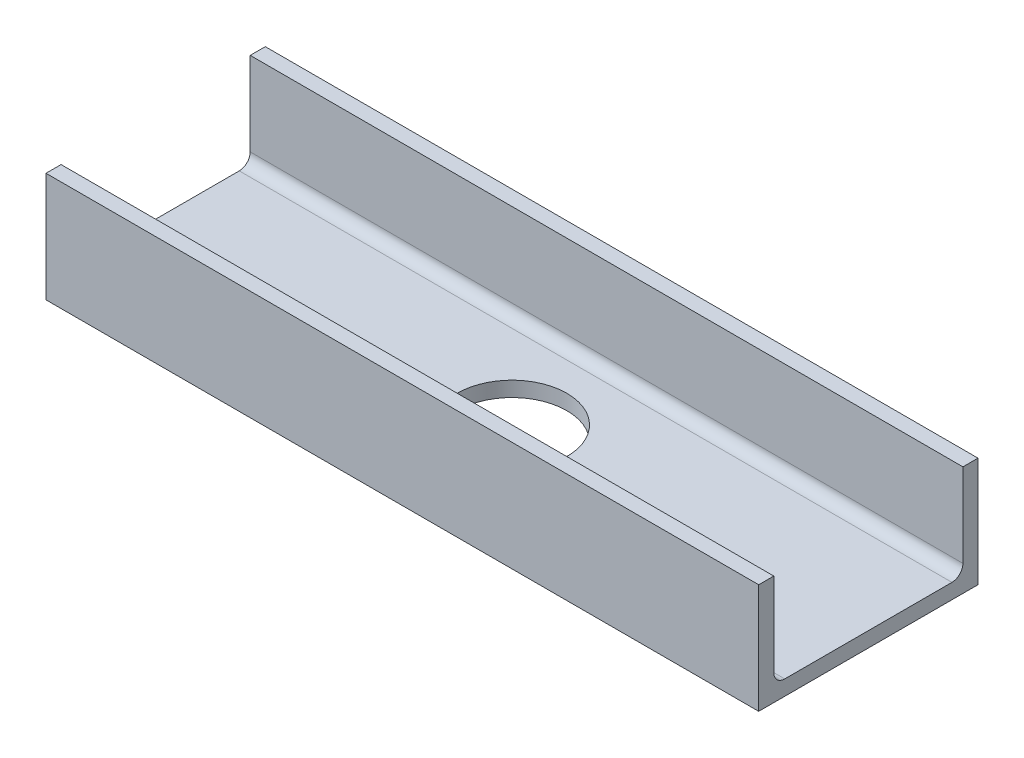
SolidWorks part; units mm, degrees
ref_plane "Front Plane" through (0, 0, 0) normal (0, 0, 1) x (1, 0, 0)
ref_plane "Top Plane" through (0, 0, 0) normal (0, 1, 0) x (1, 0, 0)
ref_plane "Right Plane" through (0, 0, 0) normal (1, 0, 0) x (0, 0, -1)
sketch "Sketch1" plane through (0, 0, 0) normal (1, 0, 0) x (0, 0, -1)
  line L0 (-21.9075, 9.2075) -> (21.9075, 9.2075)
  line L1 (-25.4, -12.7) -> (25.4, -12.7)
  line L2 (-25.4, -12.7) -> (-25.4, 12.7)
  line L3 (-25.4, 12.7) -> (25.4, 12.7)
  line L4 (25.4, -12.7) -> (25.4, 12.7)
  line L5 (-25.4, -12.7) -> (25.4, 12.7) construction
  line L6 (-25.4, 12.7) -> (25.4, -12.7) construction
  line L7 (21.9075, -6.6675) -> (21.9075, 9.2075)
  line L8 (-19.3675, -9.2075) -> (19.3675, -9.2075)
  line L9 (-21.9075, -6.6675) -> (-21.9075, 9.2075)
  line L10 (-21.9075, 9.2075) -> (-21.9075, 12.7)
  line L11 (21.9075, 9.2075) -> (21.9075, 12.7)
  line L12 (21.9075, -9.2075) -> (21.9075, 9.2075) construction
  line L13 (-21.9075, -9.2075) -> (21.9075, -9.2075) construction
  line L14 (-21.9075, -9.2075) -> (-21.9075, 9.2075) construction
  arc A0 (21.9075, -6.6675) -> (19.3675, -9.2075) centre (19.3675, -6.6675) cw
  arc A1 (-19.3675, -9.2075) -> (-21.9075, -6.6675) centre (-19.3675, -6.6675) cw
  point P0 (0, 0)
  dimension "D4" = 2.54
  dimension "D1" = 25.4
  dimension "D2" = 50.8
  dimension "D3" = 3.4925
extrude "Boss-Extrude1" add sketch "Sketch1" against normal blind 165.1 contours L8 A1 L9 L10 L3 L2 L1 L4 L11 L7 A0
sketch "Sketch2" plane through (0, -12.7, 0) normal (0, -1, 0) x (1, 0, 0)
  circle A4 centre (-82.55, 0) radius 12.7
  dimension "D1" = 25.4
extrude "Cut-Extrude1" cut sketch "Sketch2" against normal blind 11.938
